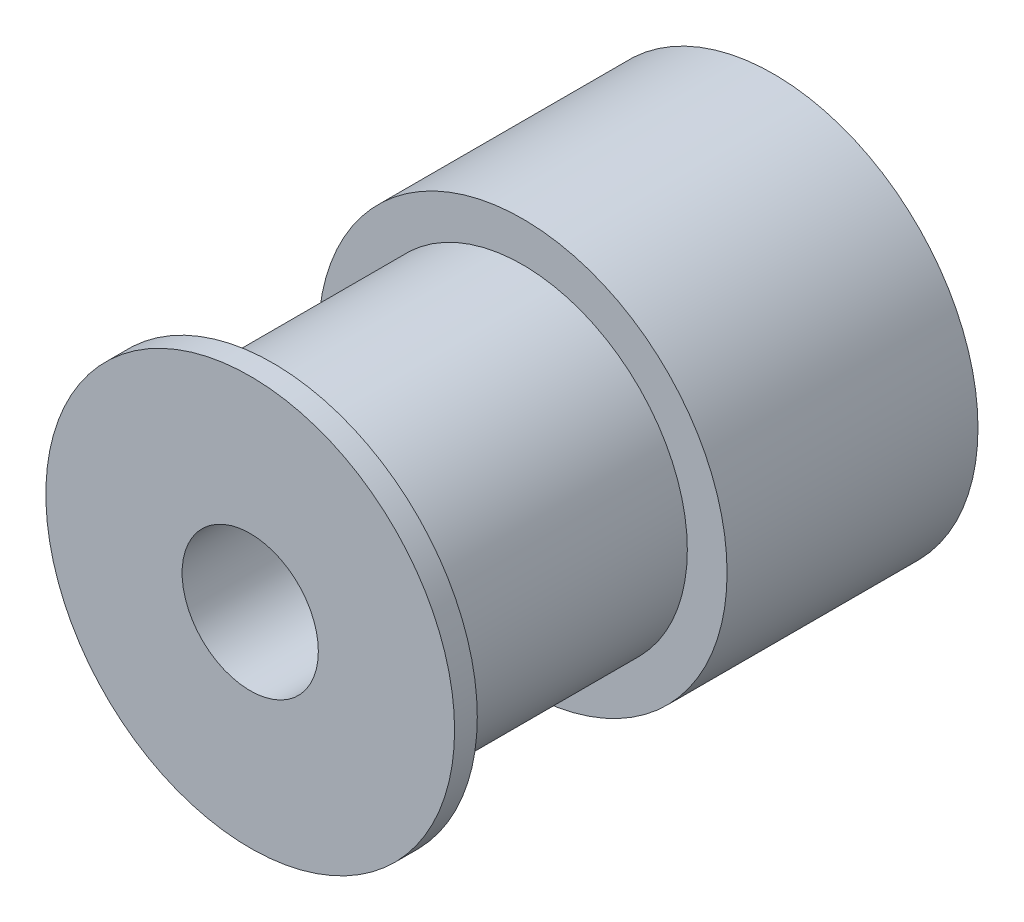
SolidWorks part; units mm, degrees
ref_plane "Front Plane" through (0, 0, 0) normal (0, 0, 1) x (1, 0, 0)
ref_plane "Top Plane" through (0, 0, 0) normal (0, 1, 0) x (1, 0, 0)
ref_plane "Right Plane" through (0, 0, 0) normal (1, 0, 0) x (0, 0, -1)
sketch "Sketch1" plane through (0, 0, 0) normal (0, 0, 1) x (1, 0, 0)
  circle A0 centre (0, 0) radius 3
  circle A1 centre (0, 0) radius 9
  dimension "D1" = 6
  dimension "D2" = 18
extrude "Boss-Extrude1" add sketch "Sketch1" along normal blind 11.05
sketch "Sketch2" plane through (0, 0, 11.05) normal (0, 0, 1) x (1, 0, 0)
  circle A0 centre (0, 0) radius 3
  circle A1 centre (0, 0) radius 7.25
  circle A2 centre (0, 0) radius 3 construction
  dimension "D1" = 14.5
extrude "Boss-Extrude2" add sketch "Sketch2" along normal blind 11
sketch "Sketch3" plane through (0, 0, 22.05) normal (0, 0, 1) x (1, 0, 0)
  circle A0 centre (0, 0) radius 3
  circle A1 centre (0, 0) radius 9
  circle A2 centre (0, 0) radius 3 construction
  dimension "D1" = 18
extrude "Boss-Extrude3" add sketch "Sketch3" along normal blind 1
sketch "Sketch4" plane through (0, 0, 0) normal (0, 1, 0) x (1, 0, 0)
  circle A0 centre (0, -4) radius 1.5
  dimension "D2" = 3
  dimension "D1" = 4
extrude "Cut-Extrude1" cut sketch "Sketch4" against normal through all
scale "Echelle1" scale about centroid uniform scaling yes scale factor 2
scale "Echelle2" scale about centroid uniform scaling yes scale factor 0.25
